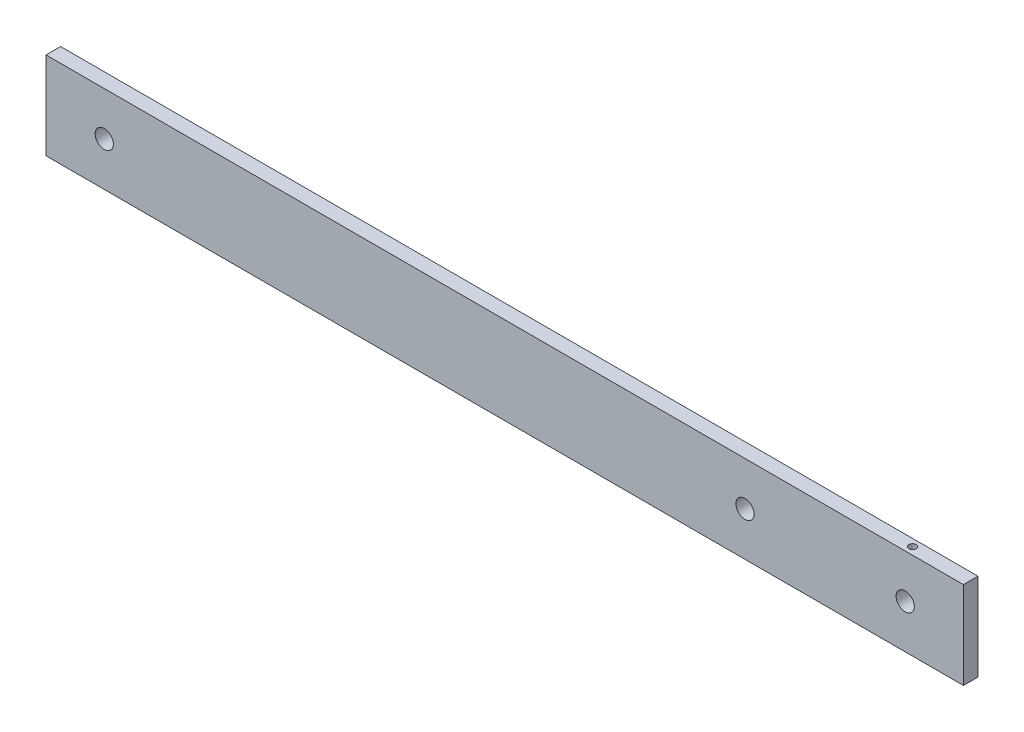
SolidWorks part; units mm, degrees
ref_plane "Front Plane" through (0, 0, 0) normal (0, 0, 1) x (1, 0, 0)
ref_plane "Top Plane" through (0, 0, 0) normal (0, 1, 0) x (1, 0, 0)
ref_plane "Right Plane" through (0, 0, 0) normal (1, 0, 0) x (0, 0, -1)
sketch "Sketch1" plane through (0, 0, 0) normal (0, 0, 1) x (1, 0, 0)
  line L1 (-609.6, 38.1) -> (190.5, 38.1)
  line L2 (-609.6, 38.1) -> (-609.6, -38.1)
  line L3 (-609.6, -38.1) -> (190.5, -38.1)
  line L4 (190.5, 38.1) -> (190.5, -38.1)
  line L5 (0, 0) -> (190.5, 0) construction
  point P10 (455.7664, -118.435)
  dimension "D1" = 76.2
  dimension "D2" = 800.1
  dimension "D3" = 190.5
extrude "Boss-Extrude1" add sketch "Sketch1" along normal blind 12.7 contours L1 L4 L3 L2
sketch "Sketch2" plane through (0, 0, 12.7) normal (0, 0, 1) x (1, 0, 0)
  line L0 (190.5, 38.1) -> (190.5, -38.1) construction
  circle A0 centre (0, 0) radius 7.9375
  circle A1 centre (-558.8, 0) radius 7.9375
  circle A2 centre (139.7, 0) radius 7.9375
  dimension "D1" = 15.875
  dimension "D2" = 15.875
  dimension "D3" = 15.875
  dimension "D4" = 558.8
  dimension "D5" = 50.8
extrude "Cut-Extrude1" cut sketch "Sketch2" against normal through all both and the other way through all
sketch "Sketch3" plane through (0, 38.1, 0) normal (0, 1, 0) x (1, 0, 0)
  line L0 (190.5, -12.7) -> (190.5, 0) construction
  circle A0 centre (139.7, -6.2124) radius 3.175
  dimension "D1" = 6.35
  dimension "D2" = 50.8
extrude "Cut-Extrude2" cut sketch "Sketch3" against normal blind 31.75 and the other way through all
